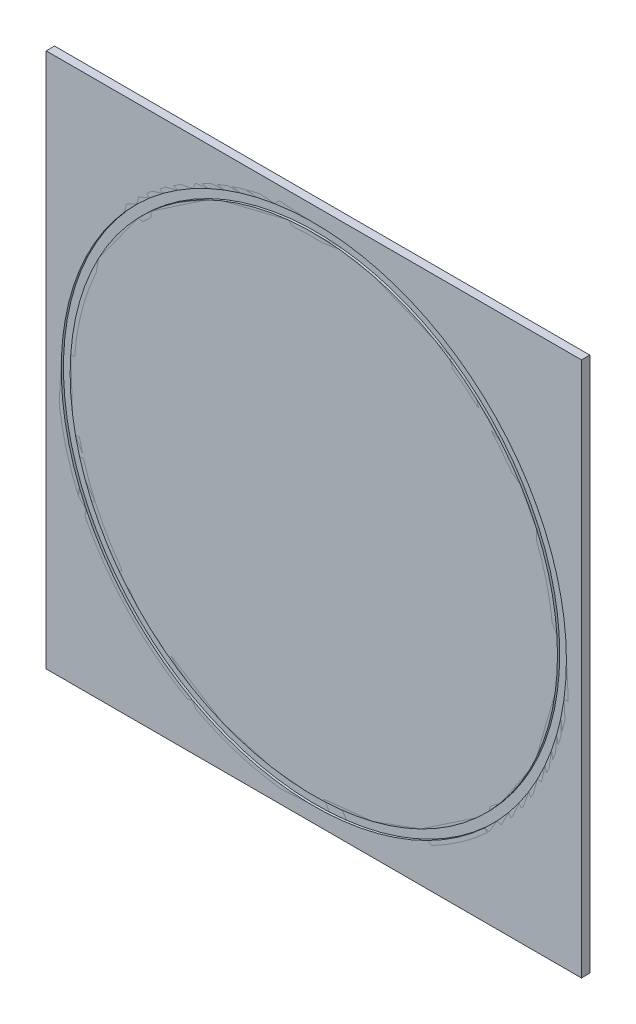
SolidWorks part; units mm, degrees
ref_plane "Front Plane" through (0, 0, 0) normal (0, 0, 1) x (1, 0, 0)
ref_plane "Top Plane" through (0, 0, 0) normal (0, 1, 0) x (1, 0, 0)
ref_plane "Right Plane" through (0, 0, 0) normal (1, 0, 0) x (0, 0, -1)
sketch "Sketch2" plane through (0, 0, 0) normal (0, 0, 1) x (1, 0, 0)
  circle A0 centre (0, 0) radius 546.1
  circle A1 centre (0, 0) radius 584.2
  dimension "D1" = 1168.4
  dimension "D2" = 1092.2
extrude "Boss-Extrude1" add sketch "Sketch2" along normal blind 19.05
sketch "Sketch3" plane through (0, 0, 19.05) normal (0, 0, 1) x (1, 0, 0)
  line L1 (609.6, 609.6) -> (-609.6, 609.6)
  line L2 (609.6, 609.6) -> (609.6, -609.6)
  line L3 (609.6, -609.6) -> (-609.6, -609.6)
  line L4 (-609.6, 609.6) -> (-609.6, -609.6)
  line L5 (609.6, 609.6) -> (-609.6, -609.6) construction
  line L6 (609.6, -609.6) -> (-609.6, 609.6) construction
  point P0 (0, 0)
  dimension "D1" = 1219.2
  dimension "D2" = 1219.2
extrude "Stock" add sketch "Sketch3" against normal blind 19.05 separate body
sketch "Sketch4" plane through (0, 0, 19.05) normal (0, 0, 1) x (1, 0, 0)
  line L1 (609.6, -609.6) -> (482.6, -609.6)
  line L2 (609.6, -609.6) -> (609.6, -482.6)
  line L3 (609.6, -482.6) -> (482.6, -482.6)
  line L4 (482.6, -609.6) -> (482.6, -482.6)
  dimension "D1" = 127
  dimension "D2" = 127
sketch "Sketch5" plane through (0, 0, 19.05) normal (0, 0, 1) x (1, 0, 0)
  circle A1 centre (0, 0) radius 575.31
  circle A2 centre (0, 0) radius 554.99
  dimension "D1" = 1109.98
  dimension "D2" = 1150.62
extrude "Cut-Extrude1" cut sketch "Sketch5" against normal blind 5.08
